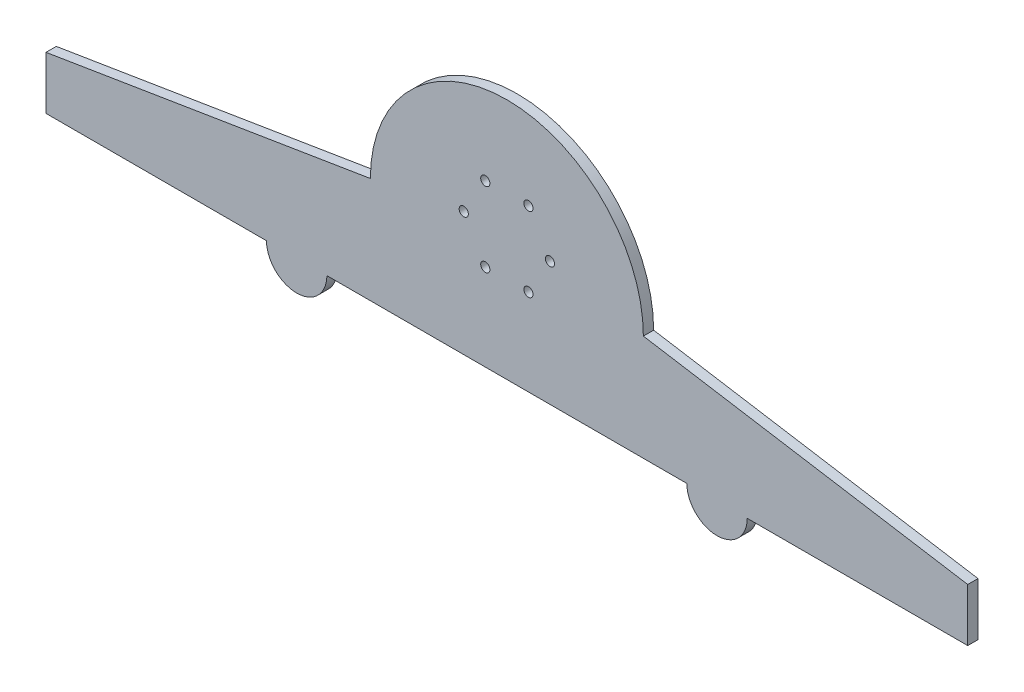
SolidWorks part; units mm, degrees
ref_plane "Front Plane" through (0, 0, 0) normal (0, 0, 1) x (1, 0, 0)
ref_plane "Top Plane" through (0, 0, 0) normal (0, 1, 0) x (1, 0, 0)
ref_plane "Right Plane" through (0, 0, 0) normal (1, 0, 0) x (0, 0, -1)
sketch "Sketch1" plane through (0, 0, 0) normal (0, 0, 1) x (1, 0, 0)
  line L10 (-170.5, 25.75) -> (-88.9257, 25.75)
  line L11 (-170.5, 25.75) -> (-170.5, 45.3316)
  line L13 (170.5, 25.75) -> (170.5, 45.3316)
  line L14 (170.5, 45.3316) -> (50.5, 64.9132)
  line L15 (-170.5, 45.3316) -> (-50.5, 64.9132)
  line L16 (88.9257, 25.75) -> (170.5, 25.75)
  line L17 (0, 64.9132) -> (0, 95.993) construction
  line L18 (-66.59, 25.75) -> (66.59, 25.75)
  arc A0 (66.59, 25.75) -> (88.9257, 25.75) centre (77.7578, 25.75) ccw
  arc A1 (-66.59, 25.75) -> (-88.9257, 25.75) centre (-77.7578, 25.75) cw
  arc A2 (50.5, 64.9132) -> (-50.5, 64.9132) centre (0, 64.9132) ccw
  circle A9 centre (15.95, 71.6132) radius 1.7
  circle A10 centre (7.975, 57.8001) radius 1.7
  circle A11 centre (-7.975, 57.8001) radius 1.7
  circle A12 centre (-15.95, 71.6132) radius 1.7
  circle A13 centre (7.975, 85.4263) radius 1.7
  circle A14 centre (-7.975, 85.4263) radius 1.7
  dimension "D1" = 133.18
  dimension "D2" = 81.5743
  dimension "D3" = 120
  dimension "D4" = 120
  dimension "D5" = 81.5743
  dimension "D6" = 19.5816
  dimension "D7" = 19.5816
  dimension "D9" = 22.3357
extrude "Boss-Extrude1" add sketch "Sketch1" along normal blind 3.8
